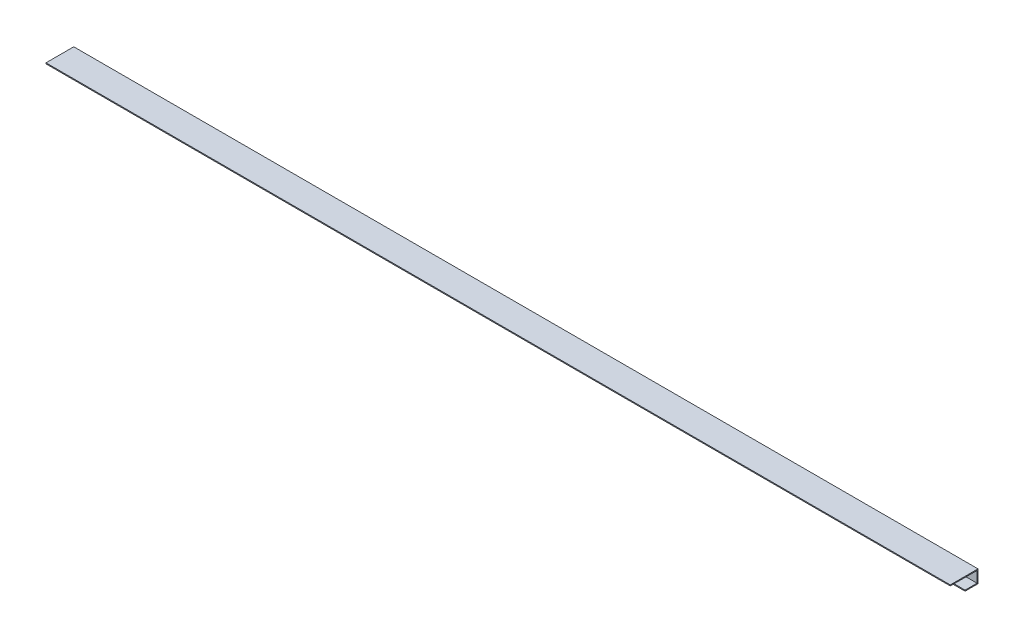
SolidWorks part; units mm, degrees
ref_plane "Front Plane" through (0, 0, 0) normal (0, 0, 1) x (1, 0, 0)
ref_plane "Top Plane" through (0, 0, 0) normal (0, 1, 0) x (1, 0, 0)
ref_plane "Right Plane" through (0, 0, 0) normal (1, 0, 0) x (0, 0, -1)
sketch "Sketch1" plane through (0, 0, 0) normal (1, 0, 0) x (0, 0, -1)
  line L0 (0, 0) -> (58, 0)
  line L1 (58, 0) -> (58, -27)
  line L2 (58, -27) -> (31, -27)
  line L3 (0, -2) -> (56, -2)
  line L4 (56, -2) -> (56, -25)
  line L5 (56, -25) -> (31, -25)
  line L6 (0, 0) -> (0, -2)
  line L7 (31, -25) -> (31, -27)
  dimension "D1" = 2
  dimension "D2" = 58
  dimension "D3" = 27
  dimension "D4" = 27
extrude "Boss-Extrude1" add sketch "Sketch1" along normal blind 1890
equation "\"door_base_short7_R1_R_open_Single_height\"=1890.0"
equation "\"D1@Boss-Extrude1\"= \"door_base_short7_L1_R_open_Single_height\""
equation "\"CarBeamWidth\"=700.0"
equation "\"WheelWidth\"=650.0"
equation "\"Wheel_FrontBoxDistance\"=1390.0"
equation "\"MetalSheet_3mm_length\"=5030.0"
equation "\"MetalSheet_3mm_width\"=1923.0"
equation "\"MetalSheet_3mm_FloorCut_L_length\"=1764.0"
equation "\"MetalSheet_3mm_FloorCut_L_disdance\"=1665.0"
equation "\"MetalSheet_3mm_FloorCut_R_length\"=1764.0"
equation "\"MetalSheet_3mm_FloorCut_R_disdance\"=1665.0"
equation "\"indoorHeight\"=1940.0"
equation "\"haveDoor_R\"=1"
equation "\"side_door_bottom_R_3mm_length\"=1934.0"
equation "\"1Bar_Side_RF_3mm_length\"=1493.0"
equation "\"1Bar_Side_RB_3mm_length\"=1493.0"
equation "\"DoorSeparator_RF_3mm_withHinge_toFrontDistance\"=1673.0"
equation "\"DoorSeparator_RF_3mm_withHinge_exist\"=1"
equation "\"DoorSeparator_RB_3mm_withHinge_toFrontDistance\"=3427.0"
equation "\"DoorSeparator_RB_3mm_withHinge_exist\"=1"
equation "\"Door_R1_L_open_Single_toFrontDistance\"=2547.5"
equation "\"Door_R1_L_open_Single_exist\"=1"
equation "\"door_base_long7_R1_L_open_Single_height\"=1890.0"
equation "\"door_base_short7_R1_L_open_Single_height\"=1890.0"
equation "\"door_base_short7_R1_L_open_Single_width\"=864"
equation "\"Door_R1_R_open_Single_toFrontDistance\"=3422.0"
equation "\"Door_R1_R_open_Single_exist\"=1"
equation "\"door_base_long7_R1_R_open_Single_height\"=1890.0"
equation "\"door_base_short7_R1_R_open_Single_width\"=864"
equation "\"x\"=66.0"
equation "\"da\"=62.0"
equation "\"SquareTube_length\"=1923.0"
equation "\"channelSteel_length\"=5030.0"
equation "\"SquareTube_inFront_AvgDistance\"=285.0"
equation "\"SquareTube_inFront_TotalCount\"=5"
equation "\"SquareTube_inFront1_cutDepth50_R\"=0.5"
equation "\"SquareTube_inFront1_cutDepth50_L\"=0.5"
equation "\"SquareTube_inFront2_cutDepth50_R\"=0.5"
equation "\"SquareTube_inFront2_cutDepth50_L\"=0.5"
equation "\"SquareTube_inFront3_cutDepth50_R\"=0.5"
equation "\"SquareTube_inFront3_cutDepth50_L\"=0.5"
equation "\"SquareTube_inFront4_cutDepth50_R\"=0.5"
equation "\"SquareTube_inFront4_cutDepth50_L\"=0.5"
equation "\"SquareTube_inFront5_cutDepth50_R\"=50"
equation "\"SquareTube_inFront5_cutDepth50_L\"=50"
equation "\"SquareTube_inFront6_cutDepth50_R\"=50"
equation "\"SquareTube_inFront6_cutDepth50_L\"=50"
equation "\"SquareTube_inFront7_cutDepth50_R\"=50"
equation "\"SquareTube_inFront7_cutDepth50_L\"=50"
equation "\"SquareTube_inFront8_cutDepth50_R\"=50"
equation "\"SquareTube_inFront8_cutDepth50_L\"=50"
equation "\"SquareTube_inFront9_cutDepth50_R\"=50"
equation "\"SquareTube_inFront9_cutDepth50_L\"=50"
equation "\"SquareTube_inFront10_cutDepth50_R\"=50"
equation "\"SquareTube_inFront10_cutDepth50_L\"=50"
equation "\"SquareTube_inFront11_cutDepth50_R\"=50"
equation "\"SquareTube_inFront11_cutDepth50_L\"=50"
equation "\"SquareTube_inFront12_cutDepth50_R\"=50"
equation "\"SquareTube_inFront12_cutDepth50_L\"=50"
equation "\"SquareTube_inFront13_cutDepth50_R\"=50"
equation "\"SquareTube_inFront13_cutDepth50_L\"=50"
equation "\"SquareTube_inFront14_cutDepth50_R\"=50"
equation "\"SquareTube_inFront14_cutDepth50_L\"=50"
equation "\"SquareTube_inBack_AvgDistance\"=333.125"
equation "\"SquareTube_inBack_TotalCount\"=9"
equation "\"SquareTube_inBack1_cutDepth50_R\"=50"
equation "\"SquareTube_inBack1_cutDepth50_L\"=50"
equation "\"SquareTube_inBack2_cutDepth50_R\"=50"
equation "\"SquareTube_inBack2_cutDepth50_L\"=50"
equation "\"SquareTube_inBack3_cutDepth50_R\"=50"
equation "\"SquareTube_inBack3_cutDepth50_L\"=50"
equation "\"SquareTube_inBack4_cutDepth50_R\"=50"
equation "\"SquareTube_inBack4_cutDepth50_L\"=50"
equation "\"SquareTube_inBack5_cutDepth50_R\"=50"
equation "\"SquareTube_inBack5_cutDepth50_L\"=50"
equation "\"SquareTube_inBack6_cutDepth50_R\"=0.5"
equation "\"SquareTube_inBack6_cutDepth50_L\"=0.5"
equation "\"SquareTube_inBack7_cutDepth50_R\"=0.5"
equation "\"SquareTube_inBack7_cutDepth50_L\"=0.5"
equation "\"SquareTube_inBack8_cutDepth50_R\"=0.5"
equation "\"SquareTube_inBack8_cutDepth50_L\"=0.5"
equation "\"boxLength\"=5100.0"
equation "\"boxWidth\"=1930.0"
equation "\"indoorHeight_para\"=25.0"
equation "\"rearLightHeight_para\"=265.0"
equation "\"doorColumnBar_A_FR_3mm_length_Cut\"=2310.0"
equation "\"A\"=0.0"
equation "\"side_door_bottom_R_3mm_toFrontDistance\"=1583.0"
equation "\"door_base_double_BL_height\"=1890.0"
equation "\"door_base_short7_BL_Single_height\"=1890.0"
equation "\"door_base_short7_BL_Single_width\"=864"
equation "\"door_base_long7_BR_Single_height\"=1890.0"
equation "\"door_base_short7_BR_Single_height\"=1890.0"
equation "\"door_base_short7_BR_Single_width\"=864"
equation "\"doorColumnBar_A_FL_3mm_length_Cut\"=2310.0"
equation "\"B\"=0.0"
equation "\"haveDoor_L\"=1"
equation "\"side_door_bottom_L_3mm_length\"=1934.0"
equation "\"side_door_bottom_L_3mm_toFrontDistance\"=1583.0"
equation "\"1Bar_Side_LF_3mm_length\"=1493.0"
equation "\"1Bar_Side_LB_3mm_length\"=1493.0"
equation "\"DoorSeparator_LF_3mm_withHinge_toFrontDistance\"=1673.0"
equation "\"DoorSeparator_LF_3mm_withHinge_exist\"=1"
equation "\"DoorSeparator_LB_3mm_withHinge_toFrontDistance\"=3427.0"
equation "\"DoorSeparator_LB_3mm_withHinge_exist\"=1"
equation "\"Door_L1_L_open_Single_toFrontDistance\"=3422.0"
equation "\"Door_L1_L_open_Single_exist\"=1"
equation "\"door_base_long7_L1_L_open_Single_height\"=1890.0"
equation "\"door_base_short7_L1_L_open_Single_height\"=1890.0"
equation "\"door_base_short7_L1_L_open_Single_width\"=864"
equation "\"Door_L1_R_open_Single_toFrontDistance\"=2547.5"
equation "\"Door_L1_R_open_Single_exist\"=1"
equation "\"door_base_long7_L1_R_open_Single_height\"=1890.0"
equation "\"door_base_short7_L1_R_open_Single_height\"=1890.0"
equation "\"door_base_short7_L1_R_open_Single_width\"=864"
